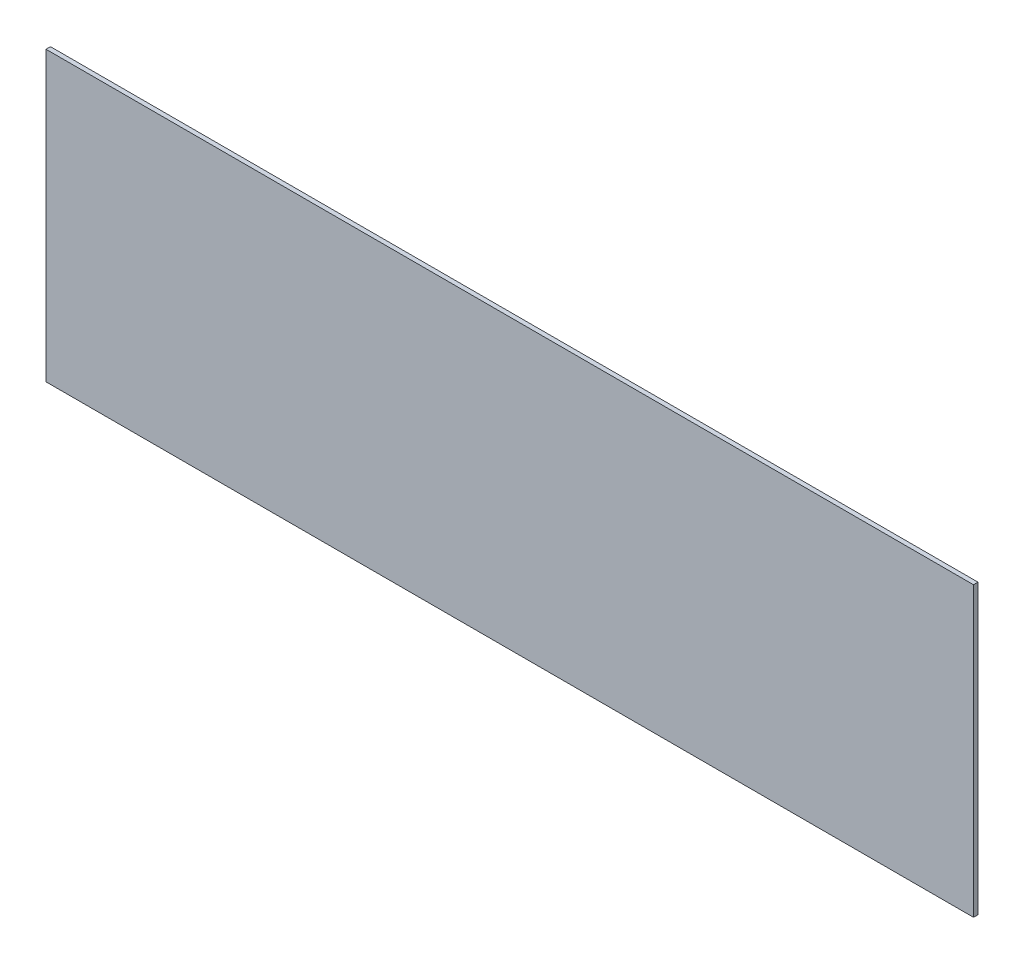
SolidWorks part; units mm, degrees
ref_plane "Front Plane" through (0, 0, 0) normal (0, 0, 1) x (1, 0, 0)
ref_plane "Top Plane" through (0, 0, 0) normal (0, 1, 0) x (1, 0, 0)
ref_plane "Right Plane" through (0, 0, 0) normal (1, 0, 0) x (0, 0, -1)
sketch "Sketch1" plane through (0, 0, 0) normal (0, 0, 1) x (1, 0, 0)
  line L1 (0, 0) -> (-657.606, 0)
  line L2 (0, 0) -> (0, 204.216)
  line L3 (0, 204.216) -> (-657.606, 204.216)
  line L4 (-657.606, 0) -> (-657.606, 204.216)
  dimension "D1" = 657.606
  dimension "D2" = 204.216
extrude "Boss-Extrude1" add sketch "Sketch1" along normal blind 3.175
